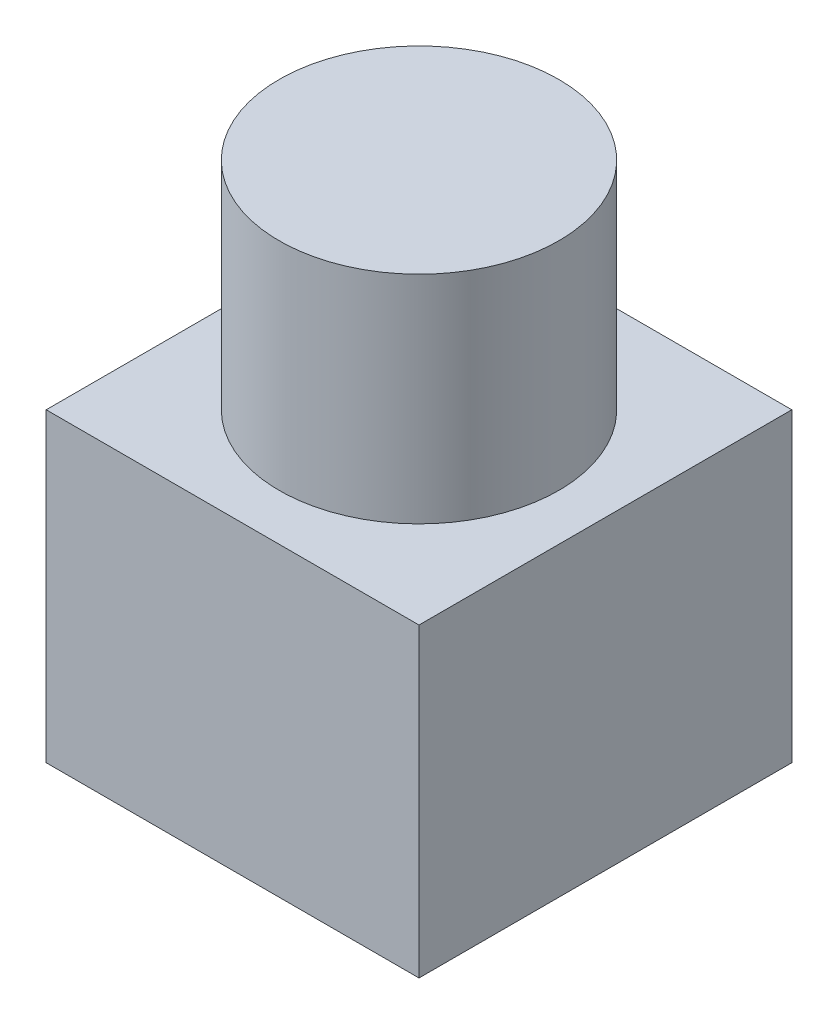
SolidWorks part; units mm, degrees
ref_plane "Front Plane" through (0, 0, 0) normal (0, 0, 1) x (1, 0, 0)
ref_plane "Top Plane" through (0, 0, 0) normal (0, 1, 0) x (1, 0, 0)
ref_plane "Right Plane" through (0, 0, 0) normal (1, 0, 0) x (0, 0, -1)
sketch "Sketch1" plane through (0, 0, 0) normal (0, 1, 0) x (1, 0, 0)
  line L1 (-25, -25) -> (25, -25)
  line L2 (-25, -25) -> (-25, 25)
  line L3 (-25, 25) -> (25, 25)
  line L4 (25, -25) -> (25, 25)
  line L5 (-25, -25) -> (25, 25) construction
  line L6 (-25, 25) -> (25, -25) construction
  point P0 (0, 0)
  dimension "D1" = 50
  dimension "D2" = 50
extrude "Boss-Extrude1" add sketch "Sketch1" along normal blind 41
sketch "Sketch2" plane through (0, 41, 0) normal (0, 1, 0) x (1, 0, 0)
  circle A0 centre (0, 0) radius 18.75
  dimension "D1" = 37.5
extrude "Boss-Extrude2" add sketch "Sketch2" along normal blind 29
